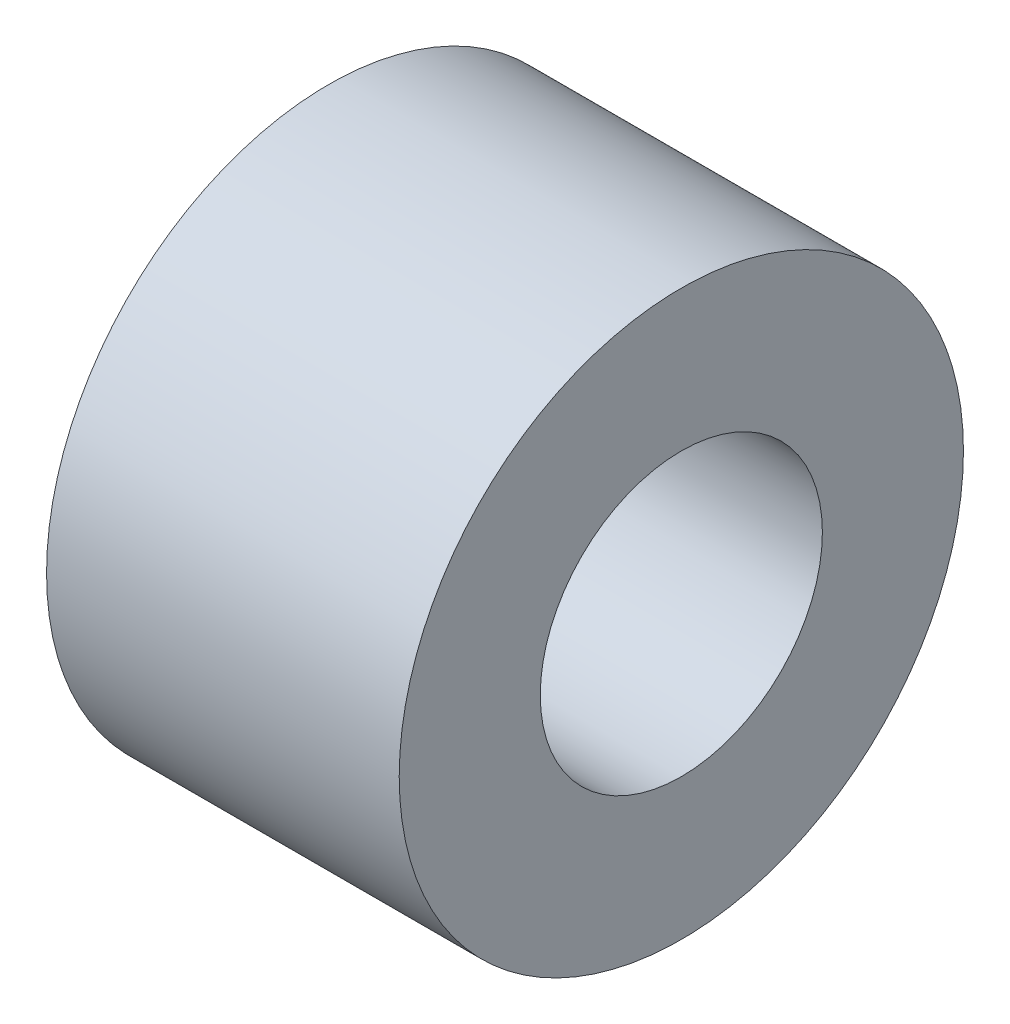
SolidWorks part; units mm, degrees
ref_plane "Front Plane" through (0, 0, 0) normal (0, 0, 1) x (1, 0, 0)
ref_plane "Top Plane" through (0, 0, 0) normal (0, 1, 0) x (1, 0, 0)
ref_plane "Right Plane" through (0, 0, 0) normal (1, 0, 0) x (0, 0, -1)
sketch "Sketch1" plane through (0, 0, 0) normal (1, 0, 0) x (0, 0, -1)
  circle A0 centre (0, 0) radius 203.2
  circle A1 centre (0, 0) radius 101.6
  dimension "D1" = 406.4
  dimension "D2" = 203.2
extrude "Boss-Extrude1" add sketch "Sketch1" along normal mid plane 254
